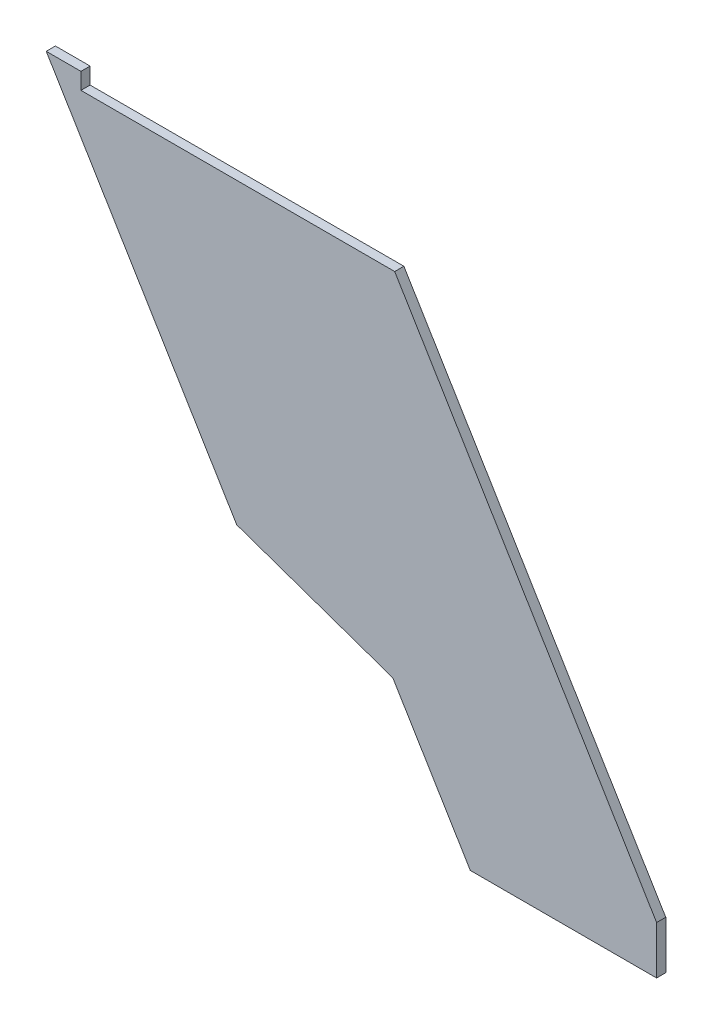
SolidWorks part; units mm, degrees
material "Oak"
ref_plane "Front Plane" through (0, 0, 0) normal (0, 0, 1) x (1, 0, 0)
ref_plane "Top Plane" through (0, 0, 0) normal (0, 1, 0) x (1, 0, 0)
ref_plane "Right Plane" through (0, 0, 0) normal (1, 0, 0) x (0, 0, -1)
sketch "Sketch1" plane through (0, 0, 0) normal (0, 0, 1) x (1, 0, 0)
  line L0 (163.7134, -144.2244) -> (163.7134, -118.0306)
  line L1 (163.7134, -118.0306) -> (20.8892, 118.0306)
  line L2 (20.8892, 118.0306) -> (-150.2306, 118.0306)
  line L3 (-150.2306, 118.0306) -> (-150.2306, 127.0222)
  line L4 (-150.2306, 127.0222) -> (-169.1536, 127.0222)
  line L5 (-169.1536, 127.0222) -> (-65.2806, -44.6601)
  line L6 (-65.2806, -44.6601) -> (19.852, -74.3744)
  line L7 (19.852, -74.3744) -> (62.1134, -144.2244)
  line L8 (62.1134, -144.2244) -> (163.7134, -144.2244)
  line L9 (92.3013, 0) -> (-92.3013, 0) construction
  point P3 (0, 0)
  point P10 (163.7134, -131.1275)
  dimension "D1" = 101.6
  dimension "D2" = 26.1937
  dimension "D3" = 262.255
  dimension "D4" = 142.8242
  dimension "D5" = 69.85
  dimension "D6" = 200.66
  dimension "D7" = 8.9916
  dimension "D8" = 18.923
  dimension "D9" = 171.1198
extrude "Boss-Extrude1" add sketch "Sketch1" along normal mid plane 5
